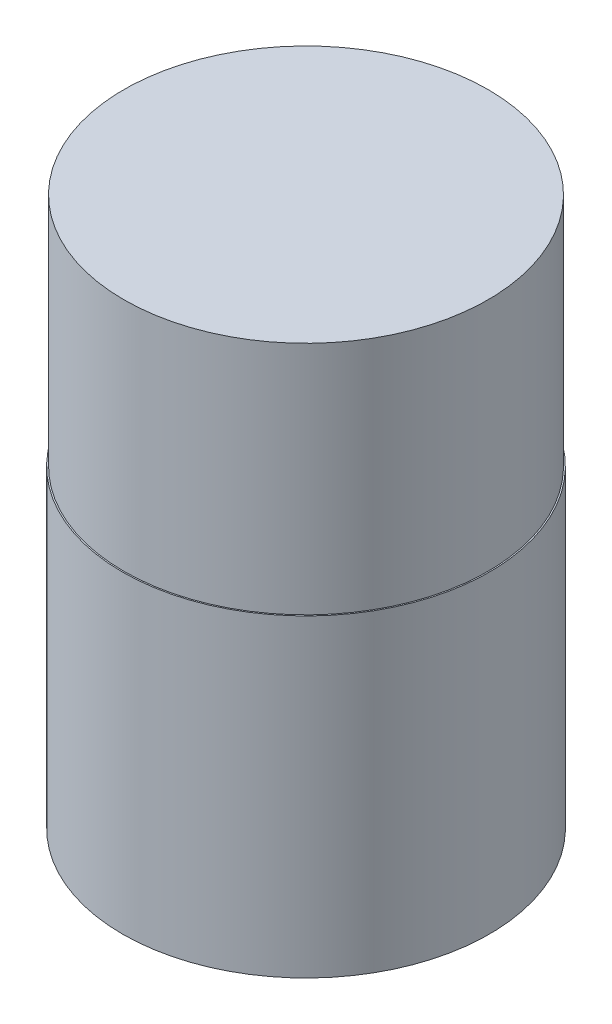
SolidWorks part; units mm, degrees
ref_plane "Front Plane" through (0, 0, 0) normal (0, 0, 1) x (1, 0, 0)
ref_plane "Top Plane" through (0, 0, 0) normal (0, 1, 0) x (1, 0, 0)
ref_plane "Right Plane" through (0, 0, 0) normal (1, 0, 0) x (0, 0, -1)
sketch "Sketch1" plane through (0, 0, 0) normal (0, 1, 0) x (1, 0, 0)
  circle A0 centre (0, 0) radius 5.9436
  dimension "D1" = 11.8872
extrude "Boss-Extrude1" add sketch "Sketch1" along normal blind 10.16
sketch "Sketch2" plane through (0, 10.16, 0) normal (0, 1, 0) x (1, 0, 0)
  line L0 (0, 0) -> (0, -5.9436) construction
  circle A0 centre (0, 0) radius 5.9
  circle A1 centre (0, 0) radius 5.9436 construction
  dimension "D1" = 11.8
extrude "Boss-Extrude2" add sketch "Sketch2" along normal blind 7.62
